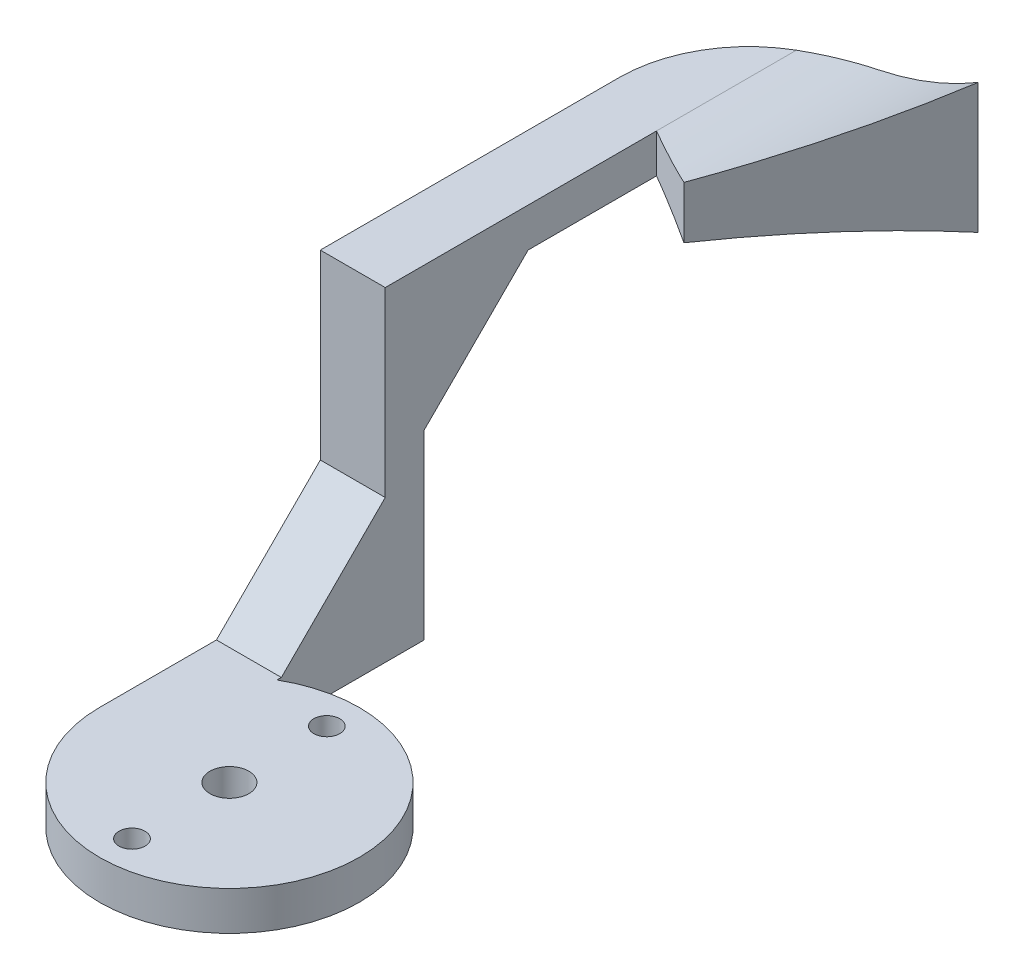
SolidWorks part; units mm, degrees
ref_plane "Front Plane" through (0, 0, 0) normal (0, 0, 1) x (1, 0, 0)
ref_plane "Top Plane" through (0, 0, 0) normal (0, 1, 0) x (1, 0, 0)
ref_plane "Right Plane" through (0, 0, 0) normal (1, 0, 0) x (0, 0, -1)
sketch "Sketch1" plane through (0, 0, 0) normal (0, 1, 0) x (1, 0, 0)
  line L0 (-10, 0) -> (-10, 20)
  line L1 (-10, 20) -> (-5, 20)
  line L2 (-5, 20) -> (-5, 8.6603)
  arc A0 (-10, 0) -> (-5, 8.6603) centre (0, 0) ccw
  circle A1 centre (0, 0) radius 1.5
  dimension "D1" = 20
  dimension "D4" = 3
  dimension "D2" = 5
  dimension "D3" = 20
extrude "Boss-Extrude1" add sketch "Sketch1" along normal blind 3
sketch "Sketch2" plane through (-10, 0, 0) normal (-1, 0, 0) x (0, 0, 1)
  line L0 (-8.6603, 0) -> (-20, 0) construction
  line L1 (-17, 0) -> (-20, 0)
  line L2 (-17, 11) -> (-17, 25)
  line L3 (-17, 25) -> (-20, 25)
  line L4 (-20, 0) -> (-20, 14)
  line L5 (-28, 22) -> (-20, 14)
  line L6 (-17, 25) -> (-30, 25)
  line L7 (-17, 25) -> (-17, 11)
  line L8 (-28, 22) -> (-30, 22)
  line L9 (-30, 25) -> (-30, 22)
  line L10 (-8.6603, 3) -> (-20, 3) construction
  line L11 (-18.5, 0) -> (-18.5, 25) construction
  line L12 (-17, 11) -> (-9, 3)
  line L13 (-30, 25) -> (-20, 25)
  line L14 (-9, 3) -> (-9, 0)
  line L15 (-9, 0) -> (-17, 0)
  point P19 (-18.5, 12.5)
  line M9 (-20, 0) -> (0, 0)
  line M11 (0, 3) -> (-20, 3)
  line M12 (-20, 3) -> (-20, 0)
  dimension "D1" = 3
  dimension "D2" = 3
  dimension "D3" = 30
  dimension "D4" = 25
  dimension "D5" = 45
extrude "Boss-Extrude2" add sketch "Sketch2" against normal blind 5 contours L11 M9 M11 M12 | L11 L1 L14 M9 M11 | L11 L12 L2 L3 M11 | L11 L6 L9 L8 L5 L4 M11
sketch "Sketch4" plane through (0, 25, 0) normal (0, 1, 0) x (1, 0, 0)
  line L0 (-5, 17) -> (-10, 17)
  line L1 (-10, 17) -> (-10, 40)
  line L3 (0, 50) -> (0, 35)
  line L4 (0, 35) -> (-5, 37.8868)
  line L5 (-5, 37.8868) -> (-5, 30)
  line L9 (-10, 30) -> (-10, 17)
  line L10 (-10, 17) -> (-5, 17)
  line L11 (-5, 17) -> (-5, 30)
  line L12 (-5, 30) -> (-10, 30)
  line L15 (-5, 17) -> (-5, 30)
  arc A0 (-10, 40) -> (0, 50) centre (0, 40) cw
  dimension "D1" = 60
  dimension "D2" = 5
  dimension "D3" = 15
  dimension "D4" = 50
  dimension "D5" = 0
extrude "Boss-Extrude3" add sketch "Sketch4" against normal up to surface (3 mm away) up to face at (-7.5, 22, -29)
sketch "Sketch5" plane through (0, 25, 0) normal (0, 1, 0) x (1, 0, 0)
  line L0 (-5, 37.8868) -> (-10, 37.8868)
  line L1 (-10, 17) -> (-10, 40) construction
  line L2 (-10, 37.8868) -> (-10, 40)
  line L4 (0, 35) -> (-5, 37.8868)
  line L6 (0, 35) -> (0, 50) construction
  line L7 (0, 50) -> (7.6429, 50)
  line L8 (7.6429, 50) -> (0, 35)
  arc A0 (-10, 40) -> (0, 50) centre (0, 40) cw
  dimension "D1" = 27
extrude "Boss-Extrude4" add sketch "Sketch5" along normal mid plane 10 from offset 1.5 offset against normal yes
ref_plane "Plane1" through (0, 0, -35) normal (0, 0, -1) x (-1, 0, 0)
sketch "Sketch6" plane through (0, 0, -35) normal (0, 0, 1) x (1, 0, 0)
  line L0 (-10, 25) -> (-5, 25)
  line L1 (7.6429, 28.5) -> (7.6429, 18.5)
  line L2 (7.6429, 23.5) -> (-10, 23.5) construction
  line L3 (-10, 11) -> (-10, 25) construction
  line L4 (-10, 22) -> (-5, 22)
  line L5 (-10, 22) -> (-10, 25)
  arc A0 (-5, 25) -> (7.6429, 28.5) centre (-5, 49.5846) ccw
  arc A1 (-5, 22) -> (7.6429, 18.5) centre (-5, -2.5846) cw
extrude "Cut-Extrude2" cut sketch "Sketch6" against normal through all flip side to cut
ref_plane "Plane2" through (0, 23.5, 0) normal (0, 1, 0) x (1, 0, 0)
sketch "Sketch7" plane through (0, 0, 0) normal (0, -1, 0) x (1, 0, 0)
  line L0 (0, 7.5) -> (0, -7.5) construction
  circle A0 centre (0, -7.5) radius 1
  circle A1 centre (0, 7.5) radius 1
  point P4 (0, 0)
  dimension "D1" = 15
  dimension "D2" = 2
extrude "Cut-Extrude3" cut sketch "Sketch7" against normal through all
